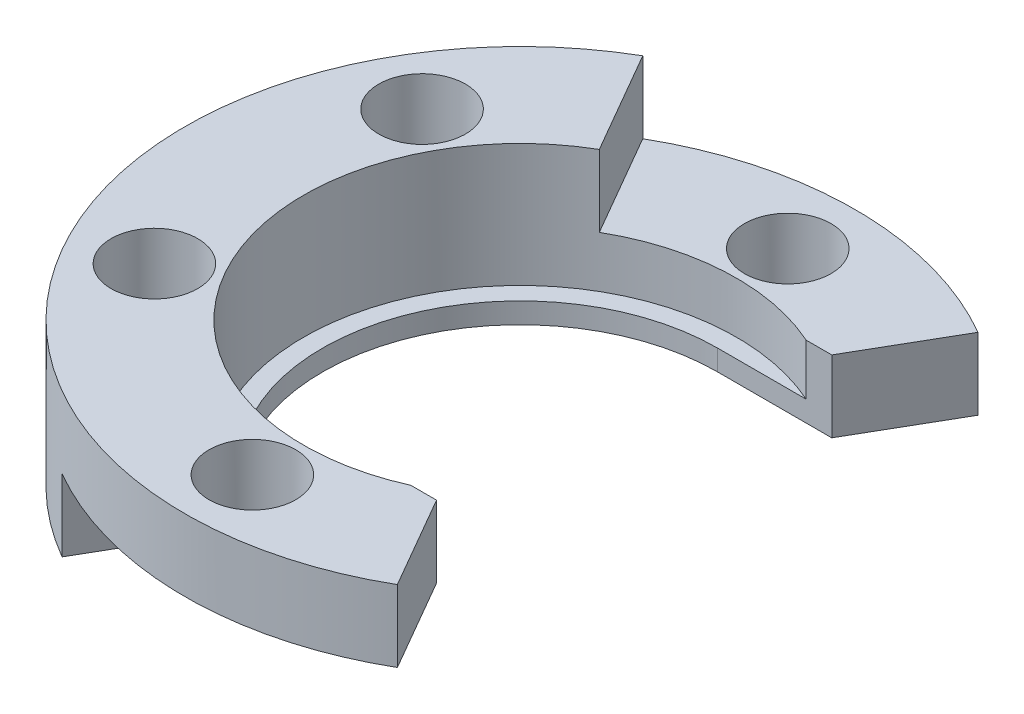
SolidWorks part; units mm, degrees
ref_plane "Front Plane" through (0, 0, 0) normal (0, 0, 1) x (1, 0, 0)
ref_plane "Top Plane" through (0, 0, 0) normal (0, 1, 0) x (1, 0, 0)
ref_plane "Right Plane" through (0, 0, 0) normal (1, 0, 0) x (0, 0, -1)
sketch "Sketch1" plane through (0, 0, 0) normal (0, 1, 0) x (1, 0, 0)
  circle A0 centre (0, 0) radius 16.891
  dimension "D1" = 33.782
extrude "Extrude1" add sketch "Sketch1" along normal blind 7.239
sketch "Sketch2" plane through (0, 0, 0) normal (0, -1, 0) x (1, 0, 0)
  circle A0 centre (0, 0) radius 10.9093
  circle A1 centre (0, 0) radius 16.891 construction
  dimension "D1" = 5.9817
extrude "Extrude2" cut sketch "Sketch2" against normal through all
sketch "Sketch3" plane through (0, 0, 0) normal (0, -1, 0) x (1, 0, 0)
  circle A0 centre (0, 0) radius 9.9568
  circle A1 centre (0, 0) radius 10.9093
  circle A2 centre (0, 0) radius 16.891 construction
  dimension "D1" = 6.9342
extrude "Extrude3" add sketch "Sketch3" against normal blind 1.0414
sketch "Sketch4" plane through (0, 7.239, 0) normal (0, 1, 0) x (1, 0, 0)
  circle A0 centre (0, 13.4874) radius 2.1844
  dimension "D1" = 4.3688
  dimension "D2" = 13.4874
extrude "Extrude4" cut sketch "Sketch4" against normal through all
pattern_circular "CirPattern1" count 6 over 360 about axis through (0, 0, 0) along (0, 1, 0) of "Extrude4"
sketch "Sketch5" plane through (0, 7.239, 0) normal (0, 1, 0) x (1, 0, 0)
  line L0 (0, 9.9568) -> (23.3834, 9.9568)
  line L1 (23.3834, 9.9568) -> (23.3834, -9.9568)
  line L2 (23.3834, -9.9568) -> (0, -9.9568)
  line L3 (0, -9.9568) -> (0, 9.9568)
  circle A0 centre (0, 0) radius 9.9568 construction
extrude "Extrude6" cut sketch "Sketch5" against normal through all
sketch "Sketch8" plane through (0, 7.239, 0) normal (0, 1, 0) x (1, 0, 0)
  line L0 (0, 0) -> (17.0252, 0)
  line L1 (17.0252, 0) -> (17.0252, 29.4885)
  line L2 (17.0252, 29.4885) -> (0, 0)
  dimension "D1" = 60
extrude "Extrude7" cut sketch "Sketch8" against normal through all
mirror "Mirror1" about plane through (0, 0, 0) normal (0, 0, 1) of "Extrude7"
sketch "Sketch9" plane through (0, 7.239, 0) normal (0, 1, 0) x (1, 0, 0)
  line L0 (0, 0) -> (-11.0815, 19.1937)
  line L1 (-11.0815, 19.1937) -> (11.0815, 19.1937)
  line L2 (11.0815, 19.1937) -> (0, 0)
  line L3 (8.4455, 14.628) -> (5.7486, 9.9568) construction
  dimension "D1" = 60
extrude "Extrude8" cut sketch "Sketch9" against normal blind 3.6195
sketch "Sketch10" plane through (0, 0, 0) normal (0, -1, 0) x (1, 0, 0)
  line L0 (0, 0) -> (-13.5047, 23.3909)
  line L1 (-13.5047, 23.3909) -> (14.4109, 24.9604)
  line L2 (14.4109, 24.9604) -> (0, 0)
  line L3 (8.4455, 14.628) -> (5.7486, 9.9568) construction
  dimension "D1" = 60
extrude "Extrude9" cut sketch "Sketch10" against normal blind 3.6195
